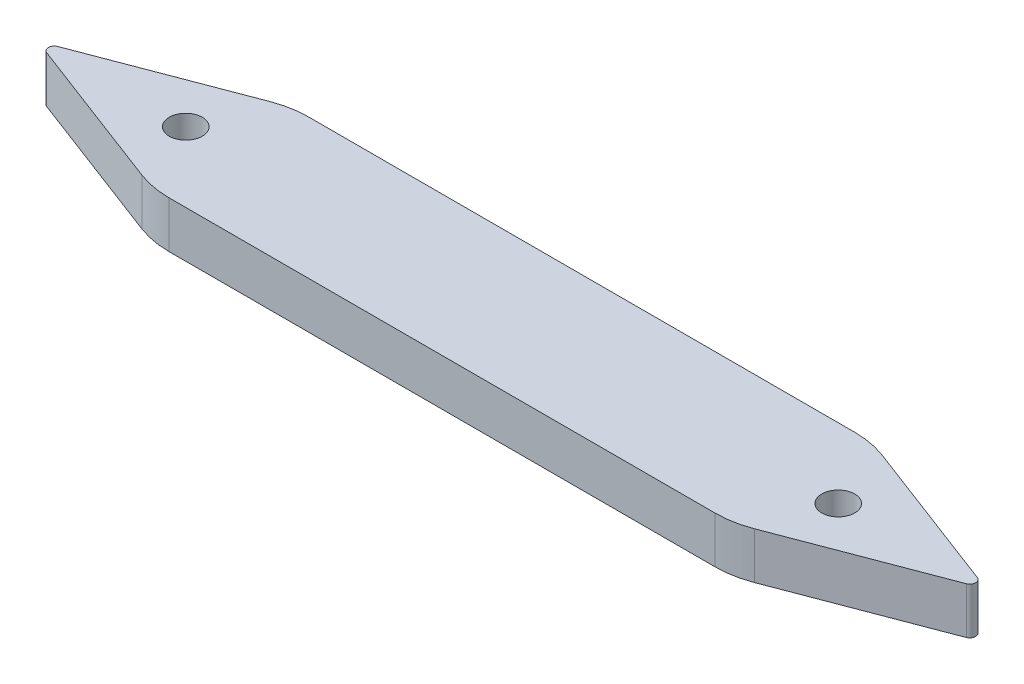
SolidWorks part; units mm, degrees
ref_plane "Front Plane" through (0, 0, 0) normal (0, 0, 1) x (1, 0, 0)
ref_plane "Top Plane" through (0, 0, 0) normal (0, 1, 0) x (1, 0, 0)
ref_plane "Right Plane" through (0, 0, 0) normal (1, 0, 0) x (0, 0, -1)
sketch "Sketch1" plane through (0, 0, 0) normal (0, 1, 0) x (1, 0, 0)
  line L0 (-119.3628, 0) -> (111.8082, 0) construction
  line L1 (0, 90.7812) -> (0, -92.2921) construction
  line L2 (37.205, 9.525) -> (-37.205, 9.525)
  line L3 (-41.7162, 8.6968) -> (-62.6498, 0.742)
  line L4 (37.205, -9.525) -> (-37.205, -9.525)
  line L5 (-41.7162, -8.6968) -> (-62.6498, -0.742)
  line L6 (41.7162, -8.6968) -> (62.6498, -0.742)
  line L7 (41.7162, 8.6968) -> (62.6498, 0.742)
  arc A0 (-37.205, 9.525) -> (-41.7162, 8.6968) centre (-37.205, -3.175) ccw
  arc A1 (-37.205, -9.525) -> (-41.7162, -8.6968) centre (-37.205, 3.175) cw
  arc A2 (-62.6498, -0.742) -> (-62.6498, 0.742) centre (-62.3679, 0) cw
  arc A3 (37.205, -9.525) -> (41.7162, -8.6968) centre (37.205, 3.175) ccw
  arc A4 (62.6498, -0.742) -> (62.6498, 0.742) centre (62.3679, 0) ccw
  arc A5 (37.205, 9.525) -> (41.7162, 8.6968) centre (37.205, -3.175) cw
  point P6 (-64.6024, 0)
  point P18 (0, -9.525)
  point P26 (0, 9.525)
  dimension "D1" = 12.7
  dimension "D2" = 0.7937
  dimension "D3" = 19.05
extrude "Boss-Extrude2" add sketch "Sketch1" along normal blind 22.225 and the other way blind 10
sketch "Sketch2" plane through (0, 0, 9.525) normal (0, 0, 1) x (1, 0, 0)
  line L0 (-37.205, 22.225) -> (37.205, 22.225) construction
  line L1 (-68.6771, 15.875) -> (84.4664, 15.875)
  line L2 (-68.6771, 15.875) -> (-68.6771, 9.525)
  line L3 (-68.6771, 9.525) -> (84.4664, 9.525)
  line L4 (84.4664, 15.875) -> (84.4664, 9.525)
  dimension "D1" = 6.35
  dimension "D2" = 6.35
extrude "Cut-Extrude1" cut sketch "Sketch2" against normal blind 4.7625
sketch "Sketch3" plane through (0, 0, -9.525) normal (0, 0, -1) x (-1, 0, 0)
  line L0 (-37.205, 22.225) -> (37.205, 22.225) construction
  line L1 (-67.7785, 15.875) -> (84.9799, 15.875)
  line L2 (-67.7785, 15.875) -> (-67.7785, 9.525)
  line L3 (-67.7785, 9.525) -> (84.9799, 9.525)
  line L4 (84.9799, 15.875) -> (84.9799, 9.525)
  dimension "D1" = 6.35
  dimension "D2" = 6.35
extrude "Cut-Extrude2" cut sketch "Sketch3" against normal blind 4.7625
fillet "Fillet3" radius 12.7 1 edges at (52.0695, 12.7, -4.7625)
fillet "Fillet4" radius 12.7 1 edges at (52.0695, 12.7, 4.7625)
fillet "Fillet5" radius 12.7 1 edges at (-52.0695, 12.7, 4.7625)
fillet "Fillet6" radius 12.7 1 edges at (-52.0695, 12.7, -4.7625)
sketch "Sketch12" plane through (0, 0, 0) normal (1, 0, 0) x (0, 0, -1)
  circle A0 centre (0, -168.402) radius 168.402
extrude "Cut-Extrude3" cut sketch "Sketch12" against normal blind 84.675 and the other way blind 94.675
sketch "Sketch19" plane through (0, 22.225, 0) normal (0, 1, 0) x (1, 0, 0)
  point P0 (-44.45, 0)
  point P1 (44.45, 0)
hole_wizard "CSK for #8 Flat Head Socket Cap Screw2" positions "Sketch21" profile "Sketch20" countersink size "#8" standard "ANSI Inch" end condition through all
sketch "Sketch21" plane through (0, 22.225, 0) normal (0, 1, 0) x (1, 0, 0)
  point P0 (-44.45, 0)
  point P3 (44.45, 0)
sketch "Sketch20" plane through (-44.45, 22.225, 0) normal (1, 0, 0) x (0, 0, 1)
  line L0 (0, 0) -> (0, 23.3241)
  line L1 (0, 23.3241) -> (2.2479, 23.3241)
  line L2 (2.2479, 23.3241) -> (2.2479, 2.659)
  line L3 (2.2479, 2.659) -> (4.5593, 0)
  line L5 (4.5593, 0) -> (0, 0)
  line L6 (-2.2479, 2.659) -> (-4.5593, 0) construction
  line L11 (0, -6.35) -> (0, 107.95) construction
  dimension "Thru Hole Dia." = 4.4958
  dimension "Thru Hole Depth" = 23.3241
  dimension "Near C'Sink Dia." = 9.1186
  dimension "Near C'Sink Angle" = 82
ref_plane "Plane6" through (0, 3.175, 0) normal (0, 1, 0) x (1, 0, 0)
ref_plane "Plane7" through (0, 9.525, 0) normal (0, 1, 0) x (1, 0, 0)
ref_plane "Plane8" through (0, 15.875, 0) normal (0, 1, 0) x (1, 0, 0)
sketch "Sketch23" plane through (0, 9.525, 0) normal (0, 1, 0) x (1, 0, 0)
  line L1 (-70.7719, 12.2668) -> (71.581, 12.2668)
  line L2 (-70.7719, 12.2668) -> (-70.7719, -11.5278)
  line L3 (-70.7719, -11.5278) -> (71.581, -11.5278)
  line L4 (71.581, 12.2668) -> (71.581, -11.5278)
extrude "Cut-Extrude4" cut sketch "Sketch23" along normal blind 27.432
sketch "Sketch24" plane through (0, 3.175, 0) normal (0, 1, 0) x (1, 0, 0)
  line L1 (-69.9346, 13.4164) -> (66.0596, 13.4164)
  line L2 (-69.9346, 13.4164) -> (-69.9346, -15.0993)
  line L3 (-69.9346, -15.0993) -> (66.0596, -15.0993)
  line L4 (66.0596, 13.4164) -> (66.0596, -15.0993)
extrude "Cut-Extrude5" cut sketch "Sketch24" against normal blind 27.432
